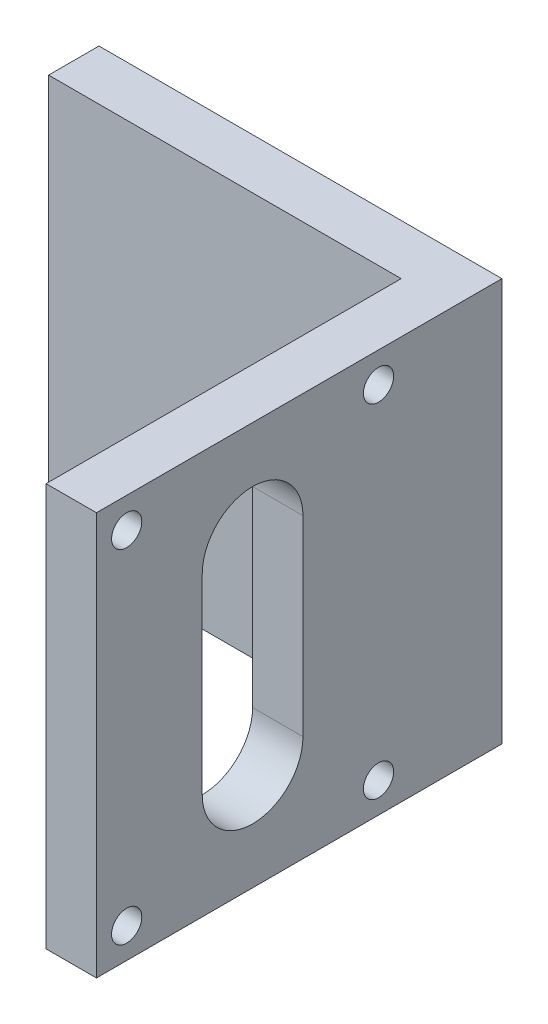
SolidWorks part; units mm, degrees
ref_plane "Front Plane" through (0, 0, 0) normal (0, 0, 1) x (1, 0, 0)
ref_plane "Top Plane" through (0, 0, 0) normal (0, 1, 0) x (1, 0, 0)
ref_plane "Right Plane" through (0, 0, 0) normal (1, 0, 0) x (0, 0, -1)
sketch "Sketch1" plane through (0, 0, 0) normal (0, 1, 0) x (1, 0, 0)
  line L0 (0, 0) -> (0, 80.5)
  line L1 (0, 80.5) -> (-80, 80.5)
  line L2 (-80, 80.5) -> (-80, 70.5)
  line L3 (0, 0) -> (-10, 0)
  line L4 (-80, 70.5) -> (-10, 70.5)
  line L5 (-10, 70.5) -> (-10, 0)
extrude "Boss-Extrude1" add sketch "Sketch1" along normal blind 80
sketch "Sketch2" plane through (0, 0, 0) normal (1, 0, 0) x (0, 0, -1)
  line L0 (6, 74) -> (56, 74)
  line L1 (0, 0) -> (6, 0)
  line L2 (0, 0) -> (0, 6)
  line L3 (0, 6) -> (6, 6)
  line L4 (6, 0) -> (6, 6)
  line L9 (0, 80) -> (6, 80)
  line L10 (0, 80) -> (0, 74)
  line L11 (0, 74) -> (6, 74)
  line L12 (6, 80) -> (6, 74)
  circle A0 centre (6, 6) radius 3
  circle A2 centre (6, 74) radius 3
  circle A3 centre (56, 74) radius 3
  circle A4 centre (56, 6) radius 3
extrude "Cut-Extrude1" cut sketch "Sketch2" against normal blind 10
sketch "Sketch3" plane through (0, 0, 0) normal (1, 0, 0) x (0, 0, -1)
  line L0 (6, 74) -> (31, 74)
  line L1 (56, 6) -> (31, 6)
  line L2 (31, 6) -> (31, 21)
  line L3 (31, 74) -> (31, 59)
  line L4 (21, 21) -> (21, 59)
  line L5 (41, 59) -> (41, 21)
  circle A0 centre (31, 59) radius 10
  circle A1 centre (31, 21) radius 10
extrude "Cut-Extrude2" cut sketch "Sketch3" against normal blind 10
